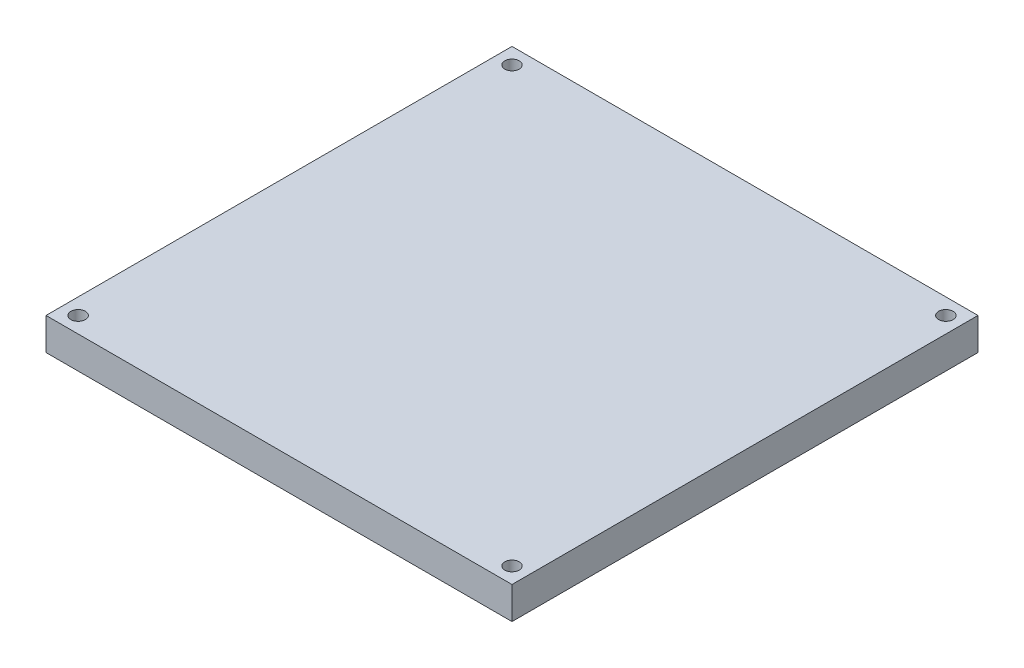
SolidWorks part; units mm, degrees
ref_plane "Front Plane" through (0, 0, 0) normal (0, 0, 1) x (1, 0, 0)
ref_plane "Top Plane" through (0, 0, 0) normal (0, 1, 0) x (1, 0, 0)
ref_plane "Right Plane" through (0, 0, 0) normal (1, 0, 0) x (0, 0, -1)
sketch "Sketch1" plane through (0, 0, 0) normal (0, 1, 0) x (1, 0, 0)
  line L1 (0, 0) -> (145, 0)
  line L2 (0, 0) -> (0, 145)
  line L3 (0, 145) -> (145, 145)
  line L4 (145, 0) -> (145, 145)
extrude "Boss-Extrude1" add sketch "Sketch1" along normal blind 10 flip side to cut
sketch "Sketch2" plane through (0, 0, 0) normal (0, 1, 0) x (1, 0, 0)
  circle A0 centre (15, 15) radius 5.5
  circle A1 centre (27.778, 15) radius 5.5
  circle A2 centre (40.556, 15) radius 5.5
  circle A3 centre (53.334, 15) radius 5.5
  circle A4 centre (66.112, 15) radius 5.5
  circle A5 centre (78.89, 15) radius 5.5
  circle A6 centre (91.668, 15) radius 5.5
  circle A7 centre (104.446, 15) radius 5.5
  circle A8 centre (117.224, 15) radius 5.5
  circle A9 centre (130.002, 15) radius 5.5
  circle A10 centre (15, 27.778) radius 5.5
  circle A11 centre (27.778, 27.778) radius 5.5
  circle A12 centre (40.556, 27.778) radius 5.5
  circle A13 centre (53.334, 27.778) radius 5.5
  circle A14 centre (66.112, 27.778) radius 5.5
  circle A15 centre (78.89, 27.778) radius 5.5
  circle A16 centre (91.668, 27.778) radius 5.5
  circle A17 centre (104.446, 27.778) radius 5.5
  circle A18 centre (117.224, 27.778) radius 5.5
  circle A19 centre (130.002, 27.778) radius 5.5
  circle A20 centre (15, 40.556) radius 5.5
  circle A21 centre (27.778, 40.556) radius 5.5
  circle A22 centre (40.556, 40.556) radius 5.5
  circle A23 centre (53.334, 40.556) radius 5.5
  circle A24 centre (66.112, 40.556) radius 5.5
  circle A25 centre (78.89, 40.556) radius 5.5
  circle A26 centre (91.668, 40.556) radius 5.5
  circle A27 centre (104.446, 40.556) radius 5.5
  circle A28 centre (117.224, 40.556) radius 5.5
  circle A29 centre (130.002, 40.556) radius 5.5
  circle A30 centre (15, 53.334) radius 5.5
  circle A31 centre (27.778, 53.334) radius 5.5
  circle A32 centre (40.556, 53.334) radius 5.5
  circle A33 centre (53.334, 53.334) radius 5.5
  circle A34 centre (66.112, 53.334) radius 5.5
  circle A35 centre (78.89, 53.334) radius 5.5
  circle A36 centre (91.668, 53.334) radius 5.5
  circle A37 centre (104.446, 53.334) radius 5.5
  circle A38 centre (117.224, 53.334) radius 5.5
  circle A39 centre (130.002, 53.334) radius 5.5
  circle A40 centre (15, 66.112) radius 5.5
  circle A41 centre (27.778, 66.112) radius 5.5
  circle A42 centre (40.556, 66.112) radius 5.5
  circle A43 centre (53.334, 66.112) radius 5.5
  circle A44 centre (66.112, 66.112) radius 5.5
  circle A45 centre (78.89, 66.112) radius 5.5
  circle A46 centre (91.668, 66.112) radius 5.5
  circle A47 centre (104.446, 66.112) radius 5.5
  circle A48 centre (117.224, 66.112) radius 5.5
  circle A49 centre (130.002, 66.112) radius 5.5
  circle A50 centre (15, 78.89) radius 5.5
  circle A51 centre (27.778, 78.89) radius 5.5
  circle A52 centre (40.556, 78.89) radius 5.5
  circle A53 centre (53.334, 78.89) radius 5.5
  circle A54 centre (66.112, 78.89) radius 5.5
  circle A55 centre (78.89, 78.89) radius 5.5
  circle A56 centre (91.668, 78.89) radius 5.5
  circle A57 centre (104.446, 78.89) radius 5.5
  circle A58 centre (117.224, 78.89) radius 5.5
  circle A59 centre (130.002, 78.89) radius 5.5
  circle A60 centre (15, 91.668) radius 5.5
  circle A61 centre (27.778, 91.668) radius 5.5
  circle A62 centre (40.556, 91.668) radius 5.5
  circle A63 centre (53.334, 91.668) radius 5.5
  circle A64 centre (66.112, 91.668) radius 5.5
  circle A65 centre (78.89, 91.668) radius 5.5
  circle A66 centre (91.668, 91.668) radius 5.5
  circle A67 centre (104.446, 91.668) radius 5.5
  circle A68 centre (117.224, 91.668) radius 5.5
  circle A69 centre (130.002, 91.668) radius 5.5
  circle A70 centre (15, 104.446) radius 5.5
  circle A71 centre (27.778, 104.446) radius 5.5
  circle A72 centre (40.556, 104.446) radius 5.5
  circle A73 centre (53.334, 104.446) radius 5.5
  circle A74 centre (66.112, 104.446) radius 5.5
  circle A75 centre (78.89, 104.446) radius 5.5
  circle A76 centre (91.668, 104.446) radius 5.5
  circle A77 centre (104.446, 104.446) radius 5.5
  circle A78 centre (117.224, 104.446) radius 5.5
  circle A79 centre (130.002, 104.446) radius 5.5
  circle A80 centre (15, 117.224) radius 5.5
  circle A81 centre (27.778, 117.224) radius 5.5
  circle A82 centre (40.556, 117.224) radius 5.5
  circle A83 centre (53.334, 117.224) radius 5.5
  circle A84 centre (66.112, 117.224) radius 5.5
  circle A85 centre (78.89, 117.224) radius 5.5
  circle A86 centre (91.668, 117.224) radius 5.5
  circle A87 centre (104.446, 117.224) radius 5.5
  circle A88 centre (117.224, 117.224) radius 5.5
  circle A89 centre (130.002, 117.224) radius 5.5
  circle A90 centre (15, 130.002) radius 5.5
  circle A91 centre (27.778, 130.002) radius 5.5
  circle A92 centre (40.556, 130.002) radius 5.5
  circle A93 centre (53.334, 130.002) radius 5.5
  circle A94 centre (66.112, 130.002) radius 5.5
  circle A95 centre (78.89, 130.002) radius 5.5
  circle A96 centre (91.668, 130.002) radius 5.5
  circle A97 centre (104.446, 130.002) radius 5.5
  circle A98 centre (117.224, 130.002) radius 5.5
  circle A99 centre (130.002, 130.002) radius 5.5
extrude "Cut-Extrude1 (100 Pockets ร 11 Depth 3mm)" cut sketch "Sketch2" along normal blind 3
sketch "Sketch3" plane through (0, 0, 0) normal (0, 1, 0) x (1, 0, 0)
  circle A0 centre (5, 5) radius 2.25
  circle A1 centre (140, 5) radius 2.25
  circle A2 centre (5, 140) radius 2.25
  circle A3 centre (140, 140) radius 2.25
extrude "Cut-Extrude2 (4 Corner Holes ร 4.5 Thru)" cut sketch "Sketch3" along normal through all
sketch "Sketch4" plane through (0, 0, 0) normal (0, 1, 0) x (1, 0, 0)
  circle A0 centre (5, 5) radius 4
  circle A1 centre (140, 5) radius 4
  circle A2 centre (5, 140) radius 4
  circle A3 centre (140, 140) radius 4
extrude "Cut-Extrude3 (4 Counterbores ร 8 Depth 4mm)" cut sketch "Sketch4" along normal blind 4
